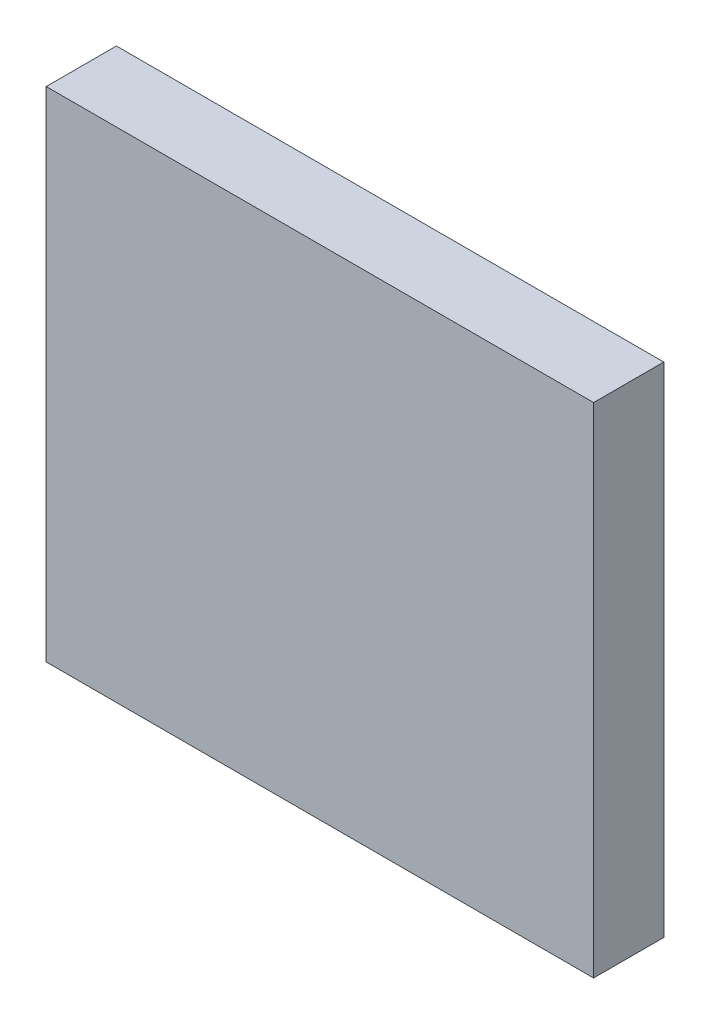
SolidWorks part; units mm, degrees
ref_plane "Front Plane" through (0, 0, 0) normal (0, 0, 1) x (1, 0, 0)
ref_plane "Top Plane" through (0, 0, 0) normal (0, 1, 0) x (1, 0, 0)
ref_plane "Right Plane" through (0, 0, 0) normal (1, 0, 0) x (0, 0, -1)
sketch "Sketch1" plane through (0, 0, 0) normal (0, 0, 1) x (1, 0, 0)
  line L0 (-2.15, 3.5016) -> (5.65, 3.5016)
  line L1 (5.65, 3.5016) -> (5.65, -3.6)
  line L2 (5.65, -3.6) -> (-2.15, -3.6)
  line L3 (-2.15, -3.6) -> (-2.15, 3.5016)
extrude "Component_Outline" add sketch "Sketch1" along normal blind 1 separate body
sketch3d "3DSketch1"
  line L0 (0, 0, 0) -> (1, 0, 0)
  line L1 (0, 0, 0) -> (0, 1, 0)
  line L2 (0, 0, 0) -> (0, 0, 1)
  point P0 (0, 0, 0)
